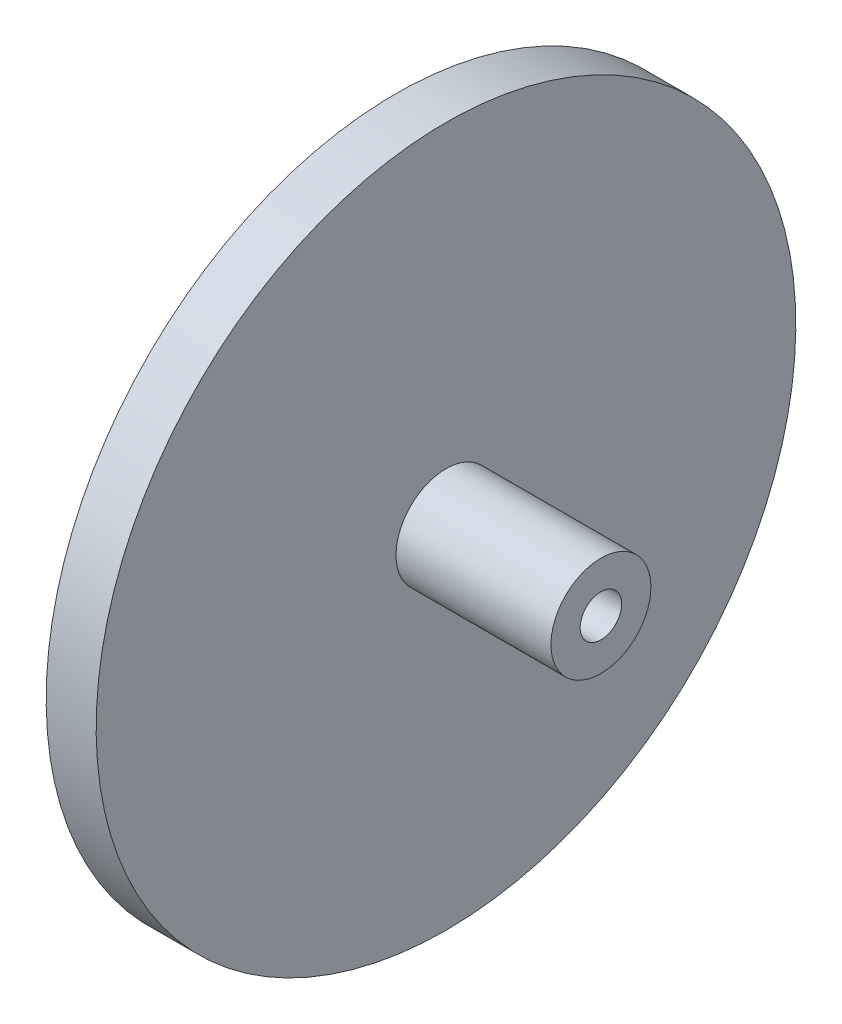
SolidWorks part; units mm, degrees
ref_plane "Front Plane" through (0, 0, 0) normal (0, 0, 1) x (1, 0, 0)
ref_plane "Top Plane" through (0, 0, 0) normal (0, 1, 0) x (1, 0, 0)
ref_plane "Right Plane" through (0, 0, 0) normal (1, 0, 0) x (0, 0, -1)
sketch "Sketch2" plane through (0, 0, 0) normal (0, 0, 1) x (1, 0, 0)
  line L5 (41.91, 44.45) -> (48.26, 44.45)
  line L8 (48.26, 44.45) -> (48.26, 6.35)
  line L9 (48.26, 6.35) -> (67.945, 6.35)
  line L10 (67.945, 6.35) -> (67.945, 0)
  line L16 (41.91, 44.45) -> (41.91, 0)
  line L17 (41.91, 0) -> (67.945, 0)
  dimension "D1" = 38.1
  dimension "D2" = 6.35
  dimension "D3" = 6.35
  dimension "D7" = 19.685
revolve "Revolve1" add sketch "Sketch2" angle 360 about L17
sketch "Sketch3" plane through (67.945, 0, 0) normal (1, 0, 0) x (0, 0, -1)
  circle A0 centre (0, 0) radius 2.6416
  dimension "D1" = 5.2832
extrude "Cut-Extrude1" cut sketch "Sketch3" against normal through all
equation "\"width_of_film\"= 1.4'a lil more than 35mm"
